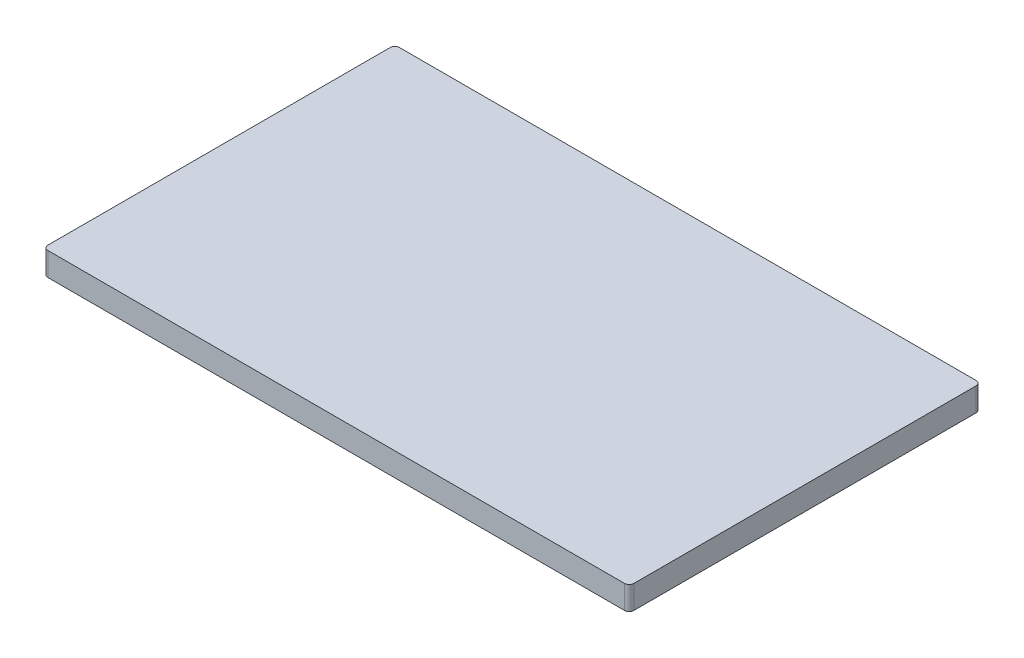
SolidWorks part; units mm, degrees
ref_plane "Front Plane" through (0, 0, 0) normal (0, 0, 1) x (1, 0, 0)
ref_plane "Top Plane" through (0, 0, 0) normal (0, 1, 0) x (1, 0, 0)
ref_plane "Right Plane" through (0, 0, 0) normal (1, 0, 0) x (0, 0, -1)
sketch "Sketch1" plane through (0, 0, 0) normal (0, 1, 0) x (1, 0, 0)
  line L1 (0, 0) -> (317.5, 0)
  line L2 (0, 0) -> (0, 190.5)
  line L3 (0, 190.5) -> (317.5, 190.5)
  line L4 (317.5, 0) -> (317.5, 190.5)
  dimension "D1" = 317.5
  dimension "D2" = 190.5
extrude "Boss-Extrude1" add sketch "Sketch1" along normal blind 12.7
fillet "Fillet1" radius 2.54 4 edges at (0, 6.35, -190.5) (0, 6.35, 0) (317.5, 6.35, -190.5) (317.5, 6.35, 0)
